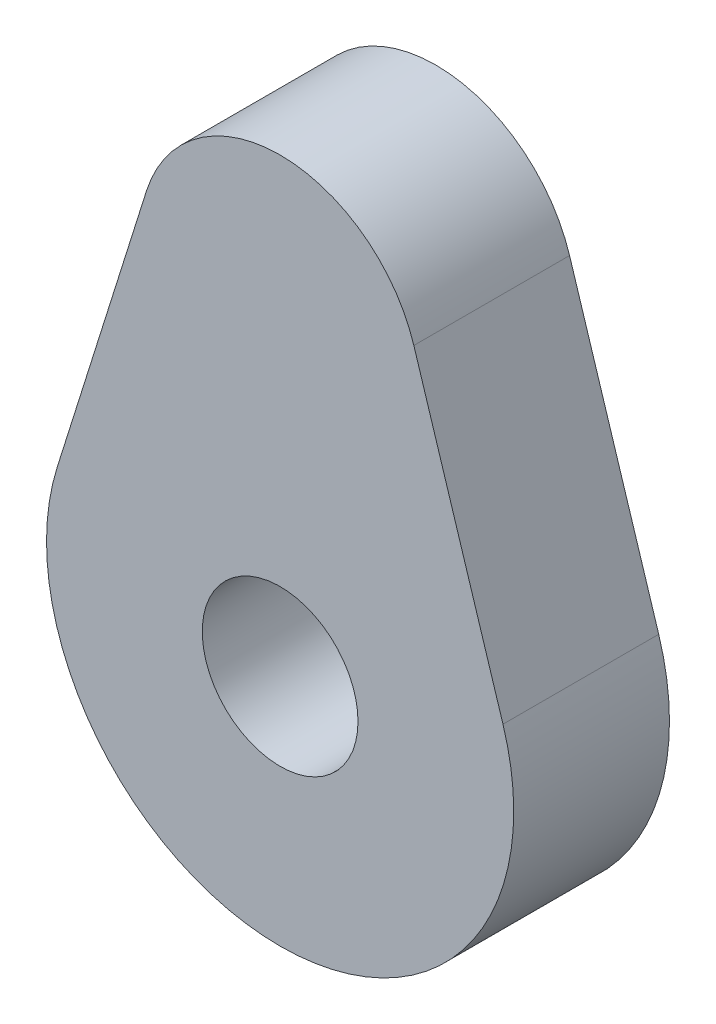
SolidWorks part; units mm, degrees
ref_plane "Front Plane" through (0, 0, 0) normal (0, 0, 1) x (1, 0, 0)
ref_plane "Top Plane" through (0, 0, 0) normal (0, 1, 0) x (1, 0, 0)
ref_plane "Right Plane" through (0, 0, 0) normal (1, 0, 0) x (0, 0, -1)
sketch "Sketch1" plane through (0, 0, 0) normal (0, 0, 1) x (1, 0, 0)
  line L0 (-21.8071, 57.658) -> (-36.3451, 11.43)
  line L1 (21.8071, 57.658) -> (36.3451, 11.43)
  line L2 (0, 50.8) -> (0, 0) construction
  arc A0 (-36.3451, 11.43) -> (36.3451, 11.43) centre (0, 0) ccw
  arc A1 (21.8071, 57.658) -> (-21.8071, 57.658) centre (0, 50.8) ccw
  circle A2 centre (0, 0) radius 12.7
  dimension "D1" = 38.1
  dimension "D3" = 22.86
  dimension "D4" = 25.4
  dimension "D2" = 50.8
extrude "Boss-Extrude1" add sketch "Sketch1" along normal blind 25.4
